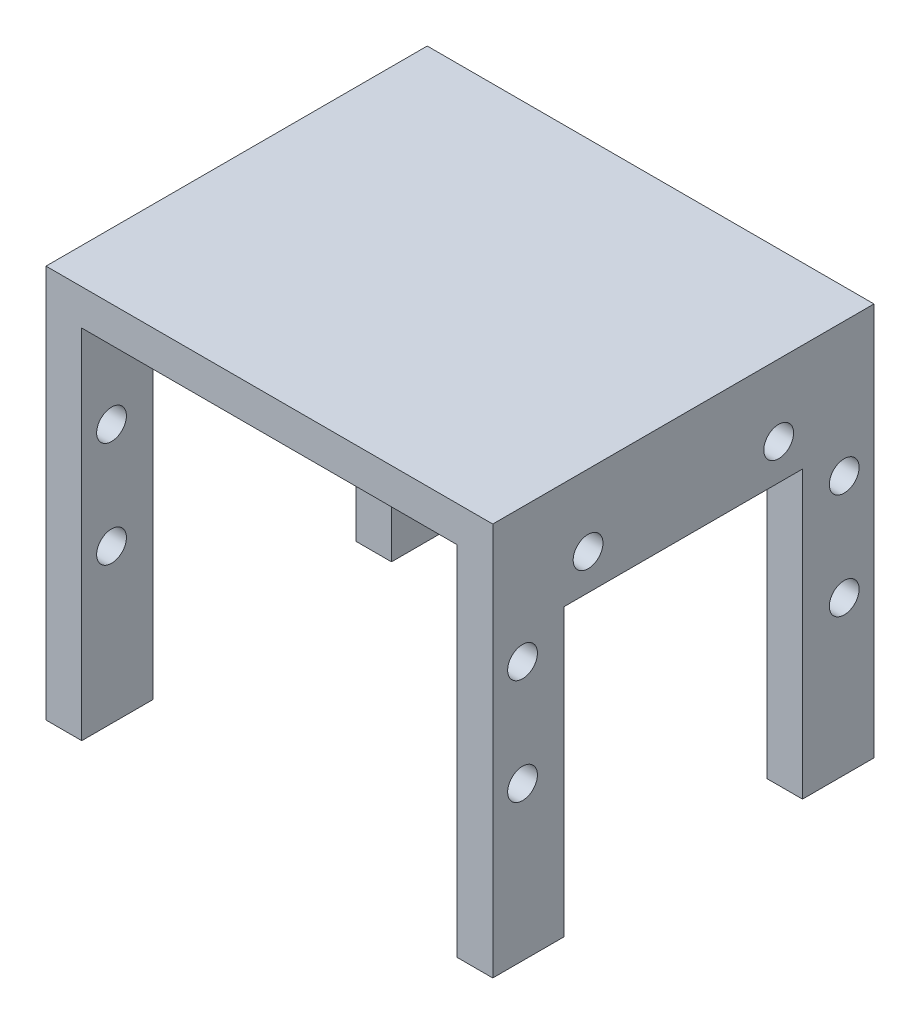
SolidWorks part; units mm, degrees
ref_plane "Front Plane" through (0, 0, 0) normal (0, 0, 1) x (1, 0, 0)
ref_plane "Top Plane" through (0, 0, 0) normal (0, 1, 0) x (1, 0, 0)
ref_plane "Right Plane" through (0, 0, 0) normal (1, 0, 0) x (0, 0, -1)
sketch "Sketch1" plane through (0, 0, 0) normal (0, 0, 1) x (1, 0, 0)
  line L0 (0, 0) -> (0, 30)
  line L1 (0, 30) -> (31.5, 30)
  line L2 (31.5, 30) -> (31.5, 0)
  line L3 (-3, 0) -> (-3, 33)
  line L4 (-3, 33) -> (34.5, 33)
  line L5 (34.5, 33) -> (34.5, 0)
  line L6 (-3, 0) -> (0, 0)
  line L7 (31.5, 0) -> (34.5, 0)
  dimension "D1" = 31.5
  dimension "D2" = 30
  dimension "D3" = 3
extrude "Boss-Extrude1" add sketch "Sketch1" along normal blind 32
sketch "Sketch2" plane through (0, 33, 0) normal (0, 1, 0) x (1, 0, 0)
  line L0 (-3, -32) -> (-3, 0) construction
  line L1 (34.5, 0) -> (-3, 0) construction
  circle A0 centre (15.75, -16) radius 10
  dimension "D1" = 20
  dimension "D3" = 16
  dimension "D2" = 18.75
sketch "Sketch3" plane through (34.5, 0, 0) normal (1, 0, 0) x (0, 0, -1)
  line L0 (-32, 0) -> (0, 0) construction
  line L1 (-26, 0) -> (-6, 0)
  line L2 (-26, 0) -> (-26, 24)
  line L3 (-26, 24) -> (-6, 24)
  line L4 (-6, 0) -> (-6, 24)
  line L5 (-32, 0) -> (-32, 33) construction
  dimension "D1" = 20
  dimension "D2" = 6
  dimension "D3" = 6
extrude "Cut-Extrude2" cut sketch "Sketch3" against normal up to surface (37.5 mm away) up to face at (-3, 16.5, 16)
sketch "Sketch4" plane through (34.5, 0, 0) normal (1, 0, 0) x (0, 0, -1)
  line L0 (-32, 0) -> (-32, 33) construction
  line L1 (0, 0) -> (0, 33) construction
  line L2 (-32, 33) -> (0, 33) construction
  circle A0 centre (-24, 27) radius 1.25
  circle A1 centre (-8, 27) radius 1.25
  circle A2 centre (-2.5, 21.75) radius 1.25
  circle A3 centre (-2.5, 12.8962) radius 1.25
  circle A4 centre (-29.5, 21.75) radius 1.25
  circle A5 centre (-29.5, 12.8962) radius 1.25
  dimension "D5" = 2.5
  dimension "D6" = 2.5
  dimension "D7" = 6
  dimension "D8" = 2.5
  dimension "D1" = 8
  dimension "D2" = 8
  dimension "D3" = 8.8538
  dimension "D4" = 5.25
extrude "Cut-Extrude3" cut sketch "Sketch4" against normal up to surface (37.5 mm away)
